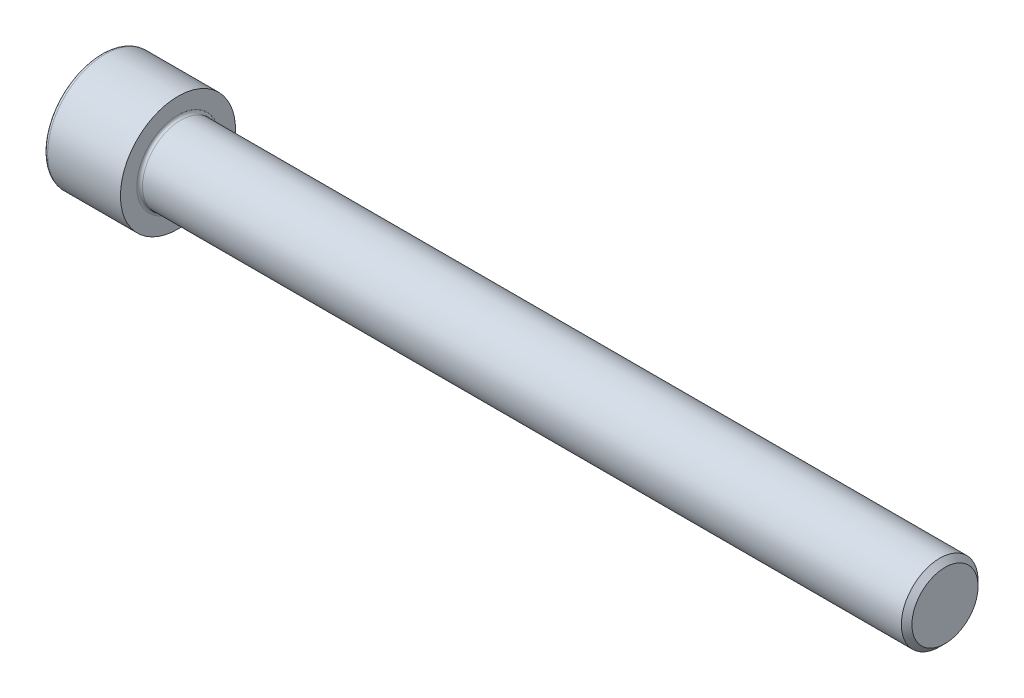
SolidWorks part; units mm, degrees
ref_plane "Plane1" through (0, 0, 0) normal (0, 0, 1) x (1, 0, 0)
ref_plane "Plane2" through (0, 0, 0) normal (0, 1, 0) x (1, 0, 0)
ref_plane "Plane3" through (0, 0, 0) normal (1, 0, 0) x (0, 0, -1)
sketch "BodySke" plane through (0, 0, 0) normal (0, 0, 1) x (1, 0, 0)
  line L0 (0, 0) -> (0, 12)
  line L1 (0, 12) -> (16, 12)
  line L2 (16, 12) -> (16, 8)
  line L3 (16, 8) -> (174.8985, 8)
  line L4 (176, 6.8985) -> (176, 0)
  line L5 (176, 0) -> (0, 0)
  line L6 (-31.75, 0) -> (127, 0) construction
  line L8 (176, 6.8985) -> (174.8985, 8)
  line L10 (176, -6.8985) -> (174.8985, -8) construction
  line L11 (18, 9.525) -> (18, 3.175) construction
  line L12 (132, 9.525) -> (132, 3.175) construction
  line L13 (116, 9.525) -> (116, 3.175) construction
  dimension "Diameter" = 16
  dimension "Head_ht" = 16
  dimension "Length" = 160
  dimension "Body_ch_ang" = 45
  dimension "Head_dia" = 24
  dimension "Minor_dia" = 13.797
  dimension "Advance" = 2
  dimension "Thread_nom" = 44
  dimension "Thread_length" = 60
revolve "Base-Revolve" add sketch "BodySke"
cosmetic thread "ThreadCosmetic" [suppressed]
fillet "Fillet1" radius 0.6 1 edges at (16, 0, 8)
fillet "Fillet2" radius 0.8 1 edges at (0, 0, 12)
sketch "Sketch2" plane through (0, 0, 0) normal (0, 0, 1) x (1, 0, 0)
  line L0 (0, 7.071) -> (8, 7.071)
  line L1 (8, 7.071) -> (12.0824, 0)
  line L2 (-31.75, 0) -> (127, 0) construction
  line L3 (12.0824, 0) -> (0, 0)
  line L4 (0, 0) -> (0, 7.071)
  line L6 (0, 0) -> (47.625, 0) construction
  dimension "D1" = 7.071
  dimension "D2" = 60
  dimension "Depth" = 8
revolve "Hex-PreBroach" cut sketch "Sketch2" angle 360 about L6
sketch "Sketch3" plane through (0, 0, 0) normal (-1, 0, 0) x (0, 0.5, 0.866)
  line L0 (4.0824, 7.071) -> (-4.0824, 7.071)
  line L1 (-4.0824, 7.071) -> (-8.1649, 0)
  line L2 (4.0824, 7.071) -> (8.1649, 0)
  line L3 (4.0824, -7.071) -> (8.1649, 0)
  line L4 (4.0824, -7.071) -> (-4.0824, -7.071)
  line L5 (-4.0824, -7.071) -> (-8.1649, 0)
  dimension "D1" = 7.071
  dimension "D2" = 7.071
  dimension "Hex_size" = 14.142
extrude "Hex" cut sketch "Sketch3" against normal blind 8
sketch "ThdSchSke" plane through (0, 0, 0) normal (0, 0, 1) x (1, 0, 0)
  line L0 (132, -6.8985) -> (131.2287, -8)
  line L1 (132, -6.8985) -> (132.7713, -8)
  line L2 (132.7713, -8) -> (132.7713, -10)
  line L3 (-3.175, 0) -> (5.1513, 0) construction
  line L4 (0, 11.2) -> (0, -11.2) construction
  line L5 (132.7713, -10) -> (131.2287, -10)
  line L6 (131.2287, -10) -> (131.2287, -8)
  dimension "Thread_minor" = 13.797
  dimension "Diameter" = 16
  dimension "Start" = 132
  dimension "SideAngle" = 55
  dimension "VeeAngle" = 70
  dimension "Overcut" = 20
revolve "ThreadSchematic" [suppressed] cut sketch "ThdSchSke" angle 360 about L3
pattern_linear "ThdSchPat" [suppressed]
equation "\"D2@Sketch3\" = \"Hex_size@Sketch3\" / 2"
equation "\"D1@Sketch3\" = \"Hex_size@Sketch3\" / 2"
equation "\"D1@Sketch2\" = \"Hex_size@Sketch3\" / 2"
equation "\"Thread_minor@ThreadCosmetic\"  =  \"Minor_dia@BodySke\""
equation "\"Depth@Sketch2\" =  \"Key_eng@Hex\""
equation "\"Thread_length@ThreadCosmetic\" = ((sgn( (\"Length@BodySke\" - \"Advance@BodySke\" * 3.0) - \"Thread_nom@BodySke\" )-1)*( (\"Length@BodySke\" - \"Advance@BodySke\" * 3.0) - \"Thread_nom@BodySke\" ))/-2+ \"Thread_nom@BodySke\""
equation "\"Thread_minor@ThdSchSke\" = \"Minor_dia@BodySke\""
equation "\"Diameter@ThdSchSke\" = \"Diameter@BodySke\""
equation "\"Overcut@ThdSchSke\" = \"Diameter@BodySke\" * 1.25"
equation "\"Start@ThdSchSke\" = \"Head_ht@BodySke\" + \"Length@BodySke\" - \"Thread_length@ThreadCosmetic\"  '---Non-countersunk---"
equation "\"Num_threads@ThdSchPat\" = int( \"Thread_length@ThreadCosmetic\" / \"Advance@BodySke\" + 0.999 )  + 1"
equation "\"Advance@ThdSchPat\" = \"Thread_length@ThreadCosmetic\" /  (\"Num_threads@ThdSchPat\" - 1) 'relax it"
equation "\"Num_threads@ThdSchPat\" = \"Num_threads@ThdSchPat\" - sgn( \"Num_threads@ThdSchPat\" - 1) '---chamfered tips only---"
